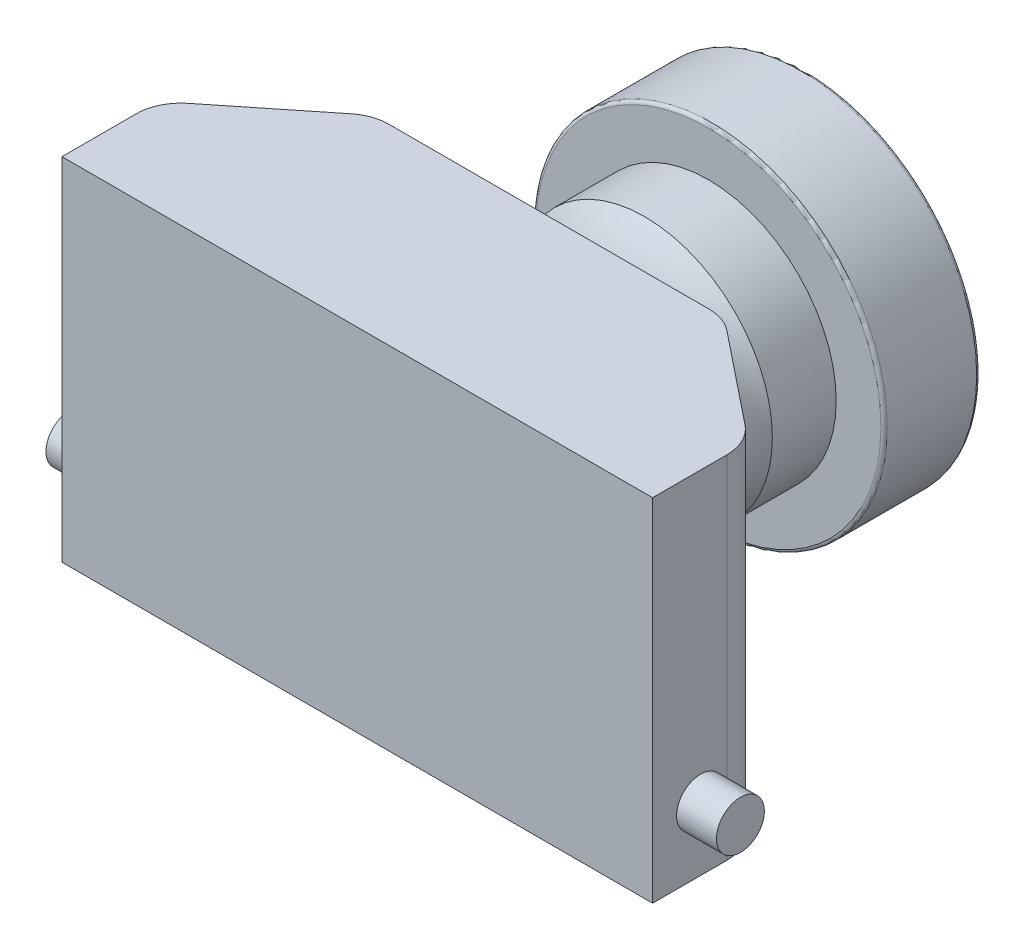
SolidWorks part; units mm, degrees
ref_plane "Front Plane" through (0, 0, 0) normal (0, 0, 1) x (1, 0, 0)
ref_plane "Top Plane" through (0, 0, 0) normal (0, 1, 0) x (1, 0, 0)
ref_plane "Right Plane" through (0, 0, 0) normal (1, 0, 0) x (0, 0, -1)
sketch "Sketch1" plane through (0, 0, 0) normal (0, 1, 0) x (1, 0, 0)
  line L0 (-9.25, 0) -> (9.25, 0)
  line L1 (-9.25, 0) -> (-9.25, 3)
  line L2 (-9.25, 3) -> (-5.5, 6)
  line L3 (-5.5, 6) -> (5.5, 6)
  line L4 (5.5, 6) -> (9.25, 3)
  line L5 (9.25, 3) -> (9.25, 0)
  line L6 (0, 0) -> (0, 18.1602) construction
  point P4 (0, 0)
  dimension "D1" = 18.5
  dimension "D2" = 3
  dimension "D3" = 3
  dimension "D4" = 3
  dimension "D5" = 11
  dimension "D6" = 3
extrude "Boss-Extrude1" add sketch "Sketch1" along normal mid plane 11
sketch "Sketch2" plane through (0, 5.5, 0) normal (0, 1, 0) x (1, 0, 0)
  line L0 (0, 0) -> (0, 11.7009) construction
  line L1 (0, 6) -> (0, 13.8)
  line L2 (5.5, 6) -> (-5.5, 6) construction
  line L3 (0, 13.8) -> (4.5, 13.8)
  line L4 (4.5, 13.8) -> (4.5, 14)
  line L5 (4.5, 14) -> (5, 14)
  line L6 (5, 14) -> (5, 11)
  line L7 (5, 11) -> (3.5, 11)
  line L8 (3.5, 11) -> (3.5, 9)
  line L9 (4.5, 6) -> (0, 6)
  arc A0 (3.5, 9) -> (4.5, 6) centre (5.8371, 8.1124) ccw
  dimension "D9" = 2.5
  dimension "D1" = 4.5
  dimension "D2" = 7.8
  dimension "D3" = 0.2
  dimension "D4" = 5
  dimension "D5" = 0.5
  dimension "D6" = 3
  dimension "D7" = 1.5
  dimension "D8" = 2
sketch "Sketch3" plane through (0, 0, 0) normal (0, 1, 0) x (1, 0, 0)
  line L0 (0, 0) -> (0, 16.4366) construction
  line L1 (4.5, 6) -> (0, 6)
  line L2 (5.5, 6) -> (-5.5, 6) construction
  line L3 (0, 6) -> (0, 13.8)
  line L4 (0, 13.8) -> (5, 13.8)
  line L5 (5, 13.8) -> (5, 14)
  line L6 (5, 14) -> (5.5, 14)
  line L7 (5.5, 14) -> (5.5, 11)
  line L8 (5.5, 11) -> (4, 11)
  line L9 (4, 11) -> (4, 9)
  arc A0 (4, 9) -> (4.5, 6) centre (6.2073, 7.8262) ccw
  dimension "D9" = 2.5
  dimension "D1" = 4.5
  dimension "D2" = 7.8
  dimension "D3" = 5
  dimension "D4" = 0.2
  dimension "D5" = 0.5
  dimension "D6" = 3
  dimension "D7" = 1.5
  dimension "D8" = 2
revolve "Revolve2" add sketch "Sketch3" angle 360 about L0
sketch "Sketch4" plane through (0, 0, 0) normal (0, 1, 0) x (1, 0, 0)
  line L0 (0, 0) -> (0, 23.2564) construction
  line L1 (0, 13.8057) -> (0, 14.8057)
  line L2 (0, 13.8057) -> (4.75, 13.8057)
  line L3 (5, 14) -> (-5, 14) construction
  arc A0 (0, 14.8057) -> (4.75, 13.8057) centre (0.0909, 3.4561) cw
  dimension "D4" = 11.35
  dimension "D1" = 4.75
  dimension "D2" = 1
  dimension "D3" = 0.1943
revolve "Revolve3" add sketch "Sketch4" angle 360 about L1
sketch "Sketch5" plane through (0, 0, 0) normal (1, 0, 0) x (0, 0, -1)
  line L0 (0, -5.5) -> (3, -5.5) construction
  line L1 (0, 5.5) -> (0, -5.5) construction
  circle A0 centre (1.5, -3.5) radius 0.75
  dimension "D1" = 2
  dimension "D3" = 1.5
  dimension "D2" = 1.5
extrude "Boss-Extrude2" add sketch "Sketch5" along normal mid plane 21
fillet "Fillet1" radius 0.1 3 edges at (5.5, 0, -11) (5.5, 0, -14) (5, 0, -14)
fillet "Fillet2" radius 1.4 4 edges at (9.25, 0, -3) (-9.25, 0, -3) (-5.5, 0, -6) (5.5, 0, -6)
